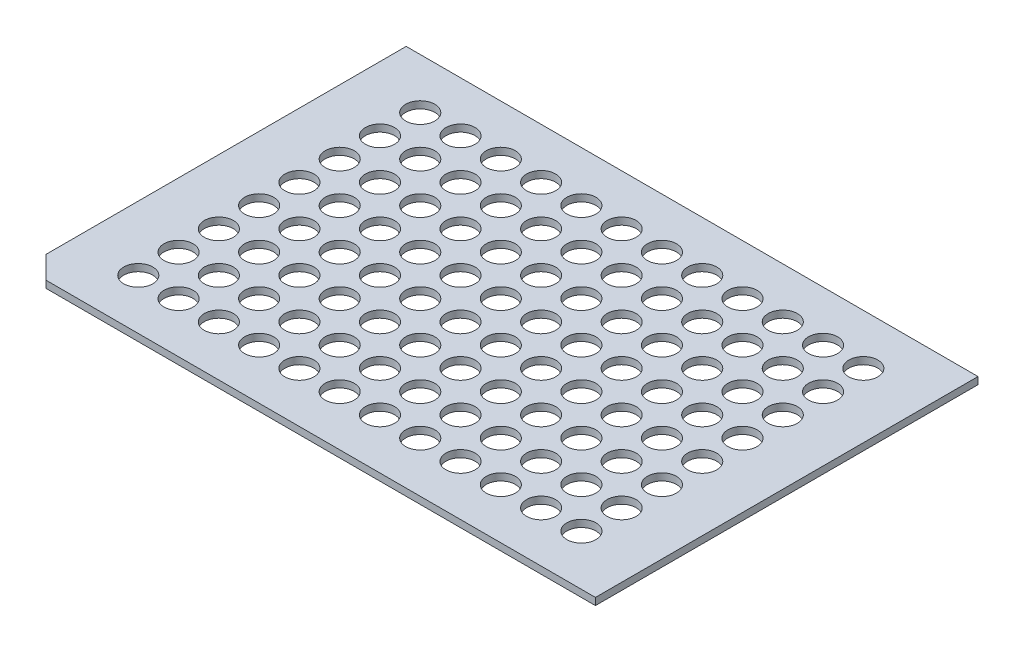
SolidWorks part; units mm, degrees
ref_plane "Front Plane" through (0, 0, 0) normal (0, 0, 1) x (1, 0, 0)
ref_plane "Top Plane" through (0, 0, 0) normal (0, 1, 0) x (1, 0, 0)
ref_plane "Right Plane" through (0, 0, 0) normal (1, 0, 0) x (0, 0, -1)
sketch "Sketch1" plane through (0, 0, 0) normal (0, 1, 0) x (1, 0, 0)
  line L0 (0, 5) -> (5, 0)
  line L1 (5, 0) -> (127.76, 0)
  line L2 (0, 5) -> (0, 85.48)
  line L3 (0, 85.48) -> (127.76, 85.48)
  line L4 (127.76, 0) -> (127.76, 85.48)
  circle A0 centre (14.38, 74.24) radius 3.25
  circle A1 centre (23.38, 74.24) radius 3.25
  circle A2 centre (32.38, 74.24) radius 3.25
  circle A3 centre (41.38, 74.24) radius 3.25
  circle A4 centre (50.38, 74.24) radius 3.25
  circle A5 centre (59.38, 74.24) radius 3.25
  circle A6 centre (68.38, 74.24) radius 3.25
  circle A7 centre (77.38, 74.24) radius 3.25
  circle A8 centre (86.38, 74.24) radius 3.25
  circle A9 centre (95.38, 74.24) radius 3.25
  circle A10 centre (104.38, 74.24) radius 3.25
  circle A11 centre (113.38, 74.24) radius 3.25
  circle A12 centre (23.38, 65.24) radius 3.25
  circle A13 centre (32.38, 65.24) radius 3.25
  circle A14 centre (41.38, 65.24) radius 3.25
  circle A15 centre (50.38, 65.24) radius 3.25
  circle A16 centre (59.38, 65.24) radius 3.25
  circle A17 centre (68.38, 65.24) radius 3.25
  circle A18 centre (77.38, 65.24) radius 3.25
  circle A19 centre (86.38, 65.24) radius 3.25
  circle A20 centre (95.38, 65.24) radius 3.25
  circle A21 centre (104.38, 65.24) radius 3.25
  circle A22 centre (113.38, 65.24) radius 3.25
  circle A23 centre (23.38, 56.24) radius 3.25
  circle A24 centre (32.38, 56.24) radius 3.25
  circle A25 centre (41.38, 56.24) radius 3.25
  circle A26 centre (50.38, 56.24) radius 3.25
  circle A27 centre (59.38, 56.24) radius 3.25
  circle A28 centre (68.38, 56.24) radius 3.25
  circle A29 centre (77.38, 56.24) radius 3.25
  circle A30 centre (86.38, 56.24) radius 3.25
  circle A31 centre (95.38, 56.24) radius 3.25
  circle A32 centre (104.38, 56.24) radius 3.25
  circle A33 centre (113.38, 56.24) radius 3.25
  circle A34 centre (23.38, 47.24) radius 3.25
  circle A35 centre (32.38, 47.24) radius 3.25
  circle A36 centre (41.38, 47.24) radius 3.25
  circle A37 centre (50.38, 47.24) radius 3.25
  circle A38 centre (59.38, 47.24) radius 3.25
  circle A39 centre (68.38, 47.24) radius 3.25
  circle A40 centre (77.38, 47.24) radius 3.25
  circle A41 centre (86.38, 47.24) radius 3.25
  circle A42 centre (95.38, 47.24) radius 3.25
  circle A43 centre (104.38, 47.24) radius 3.25
  circle A44 centre (113.38, 47.24) radius 3.25
  circle A45 centre (23.38, 38.24) radius 3.25
  circle A46 centre (32.38, 38.24) radius 3.25
  circle A47 centre (41.38, 38.24) radius 3.25
  circle A48 centre (50.38, 38.24) radius 3.25
  circle A49 centre (59.38, 38.24) radius 3.25
  circle A50 centre (68.38, 38.24) radius 3.25
  circle A51 centre (77.38, 38.24) radius 3.25
  circle A52 centre (86.38, 38.24) radius 3.25
  circle A53 centre (95.38, 38.24) radius 3.25
  circle A54 centre (104.38, 38.24) radius 3.25
  circle A55 centre (113.38, 38.24) radius 3.25
  circle A56 centre (23.38, 29.24) radius 3.25
  circle A57 centre (32.38, 29.24) radius 3.25
  circle A58 centre (41.38, 29.24) radius 3.25
  circle A59 centre (50.38, 29.24) radius 3.25
  circle A60 centre (59.38, 29.24) radius 3.25
  circle A61 centre (68.38, 29.24) radius 3.25
  circle A62 centre (77.38, 29.24) radius 3.25
  circle A63 centre (86.38, 29.24) radius 3.25
  circle A64 centre (95.38, 29.24) radius 3.25
  circle A65 centre (104.38, 29.24) radius 3.25
  circle A66 centre (113.38, 29.24) radius 3.25
  circle A67 centre (23.38, 20.24) radius 3.25
  circle A68 centre (32.38, 20.24) radius 3.25
  circle A69 centre (41.38, 20.24) radius 3.25
  circle A70 centre (50.38, 20.24) radius 3.25
  circle A71 centre (59.38, 20.24) radius 3.25
  circle A72 centre (68.38, 20.24) radius 3.25
  circle A73 centre (77.38, 20.24) radius 3.25
  circle A74 centre (86.38, 20.24) radius 3.25
  circle A75 centre (95.38, 20.24) radius 3.25
  circle A76 centre (104.38, 20.24) radius 3.25
  circle A77 centre (113.38, 20.24) radius 3.25
  circle A78 centre (23.38, 11.24) radius 3.25
  circle A79 centre (32.38, 11.24) radius 3.25
  circle A80 centre (41.38, 11.24) radius 3.25
  circle A81 centre (50.38, 11.24) radius 3.25
  circle A82 centre (59.38, 11.24) radius 3.25
  circle A83 centre (68.38, 11.24) radius 3.25
  circle A84 centre (77.38, 11.24) radius 3.25
  circle A85 centre (86.38, 11.24) radius 3.25
  circle A86 centre (95.38, 11.24) radius 3.25
  circle A87 centre (104.38, 11.24) radius 3.25
  circle A88 centre (113.38, 11.24) radius 3.25
  circle A89 centre (14.38, 65.24) radius 3.25
  circle A90 centre (14.38, 56.24) radius 3.25
  circle A91 centre (14.38, 47.24) radius 3.25
  circle A92 centre (14.38, 38.24) radius 3.25
  circle A93 centre (14.38, 29.24) radius 3.25
  circle A94 centre (14.38, 20.24) radius 3.25
  circle A95 centre (14.38, 11.24) radius 3.25
  dimension "D3" = 6.5
  dimension "D1" = 127.76
  dimension "D2" = 85.48
  dimension "D6" = 14.38
  dimension "D7" = 11.24
  dimension "D8" = 5
  dimension "D9" = 5
  dimension "D4" = 12
  dimension "D5" = 8
extrude "Boss-Extrude1" add sketch "Sketch1" along normal blind 1.5875
